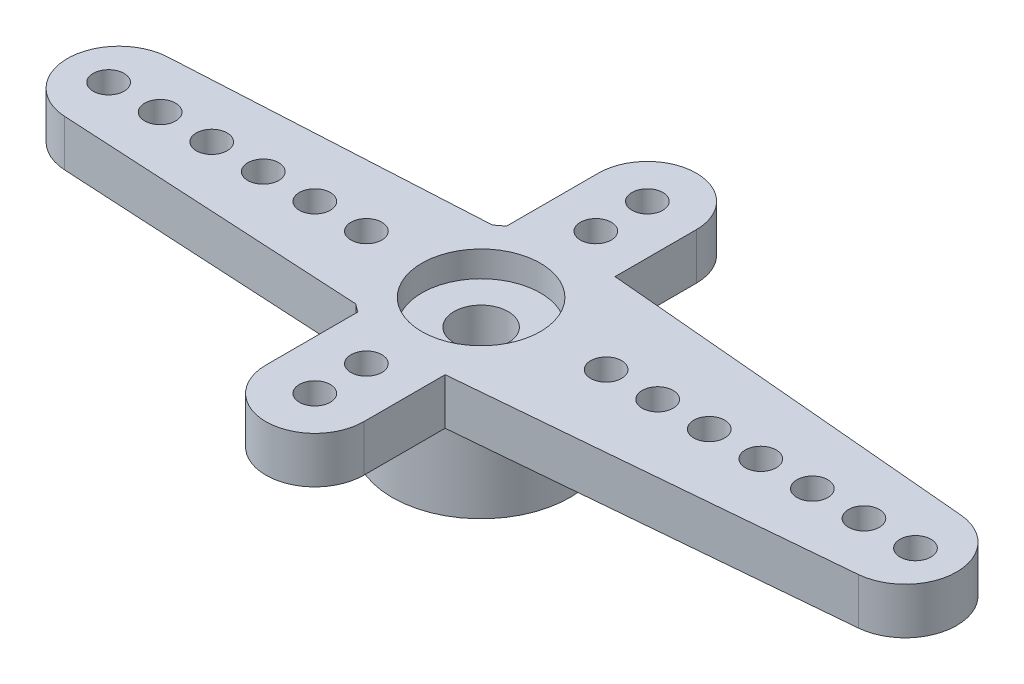
SolidWorks part; units mm, degrees
material "PVC Rígido"
ref_plane "Plano frontal" through (0, 0, 0) normal (0, 0, 1) x (1, 0, 0)
ref_plane "Plano superior" through (0, 0, 0) normal (0, 1, 0) x (1, 0, 0)
ref_plane "Plano direito" through (0, 0, 0) normal (1, 0, 0) x (0, 0, -1)
sketch "Esboço1" plane through (0, 0, 0) normal (0, 1, 0) x (1, 0, 0)
  line L0 (0, 0) -> (-14.05, 0) construction
  line L1 (-14.1591, 1.997) -> (-2.2091, 2.65)
  line L2 (-2.2091, -2.65) -> (-14.1591, -1.997)
  arc A0 (-2.2091, -2.65) -> (-2.2091, 2.65) centre (0, 0) ccw
  arc A1 (-14.1591, 1.997) -> (-14.1591, -1.997) centre (-14.05, 0) ccw
  dimension "D1" = 6.9
  dimension "D2" = 4
  dimension "D3" = 19.5
  dimension "D4" = 5.3
extrude "Ressalto-extrusão1" add sketch "Esboço1" against normal blind 1.8
sketch "Esboço2" plane through (0, -1.8, 0) normal (0, -1, 0) x (1, 0, 0)
  arc A0 (-2.2091, -2.65) -> (-2.2091, 2.65) centre (0, 0) ccw construction
  circle A1 centre (0, 0) radius 3.45
extrude "Ressalto-extrusão2" add sketch "Esboço2" along normal offset from surface (3.2 mm away) 5 up to face at (-7.242, 0, 0)
hole_wizard "Furo1" positions "Esboço9" profile "Esboço10" legacy end condition through all
sketch "Esboço9" plane through (0, 0, 0) normal (0, 1, 0) x (1, 0, 0)
  line L1 (-14.45, 0) -> (0, 0) construction
  arc A2 (-14.1591, 1.997) -> (-14.1591, -1.997) centre (-14.05, 0) ccw construction
  point P0 (-14.45, 0)
  point P19 (-16.05, 0)
  dimension "D1" = 1.6
sketch "Esboço10" plane through (-14.45, 0, 0) normal (1, 0, 0) x (0, 0, 1)
  line L0 (0, 0) -> (0, 5)
  line L1 (0, 5) -> (0.6, 5)
  line L2 (0.6, 5) -> (0.6, 0)
  line L3 (0.6, 0) -> (0, 0)
  line L4 (0, 110) -> (0, -10) construction
  dimension "Diameter" = 1.2
  dimension "Depth" = 5
pattern_linear "Padrão linear1" count 6 spacing 2 along (1, 0, 0) of "Furo1"
sketch "Esboço12" plane through (0, 0, 0) normal (0, 1, 0) x (1, 0, 0)
  line L0 (0.3041, 3.4366) -> (16.6263, 1.9922)
  line L1 (16.6263, -1.9922) -> (0.3041, -3.4366)
  arc A0 (-2.2091, -2.65) -> (-2.2091, 2.65) centre (0, 0) ccw construction
  arc A1 (0.3041, -3.4366) -> (0.3041, 3.4366) centre (0, 0) ccw
  arc A2 (16.6263, 1.9922) -> (16.6263, -1.9922) centre (16.45, 0) cw
  arc A3 (-14.1591, 1.997) -> (-14.1591, -1.997) centre (-14.05, 0) ccw construction
  dimension "D1" = 2
  dimension "D2" = 34.5
extrude "Ressalto-extrusão3" add sketch "Esboço12" against normal blind 1.8
hole_wizard "Furo2" positions "Esboço13" profile "Esboço14" legacy end condition through all
sketch "Esboço13" plane through (0, 0, 0) normal (0, 1, 0) x (1, 0, 0)
  line L0 (0, 0) -> (16.85, 0) construction
  arc A0 (16.6263, -1.9922) -> (16.6263, 1.9922) centre (16.45, 0) ccw construction
  point P0 (16.85, 0)
  point P6 (18.45, 0)
  dimension "D1" = 1.6
sketch "Esboço14" plane through (16.85, 0, 0) normal (1, 0, 0) x (0, 0, 1)
  line L0 (0, 0) -> (0, 5)
  line L1 (0, 5) -> (0.6, 5)
  line L2 (0.6, 5) -> (0.6, 0)
  line L3 (0.6, 0) -> (0, 0)
  line L4 (0, 110) -> (0, -10) construction
  dimension "Diameter" = 1.2
  dimension "Depth" = 5
pattern_linear "Padrão linear2" count 7 spacing 2 along (-1, 0, 0) of "Furo2"
sketch "Esboço16" plane through (0, 0, 0) normal (0, 1, 0) x (1, 0, 0)
  line L0 (0, -6.45) -> (0, 6.45) construction
  line L1 (-1.9, -6.45) -> (-1.9, 6.45)
  line L2 (1.9, -6.45) -> (1.9, 6.45)
  arc A0 (-1.9, -6.45) -> (1.9, -6.45) centre (0, -6.45) ccw
  arc A1 (1.9, 6.45) -> (-1.9, 6.45) centre (0, 6.45) ccw
  point P2 (0, 0)
  dimension "D2" = 16.7
  dimension "D1" = 3.8
extrude "Ressalto-extrusão4" add sketch "Esboço16" against normal up to surface (1.8 mm away) up to face at (14.85, -1.8, 0.6)
hole_wizard "Furo3" positions "Esboço17" profile "Esboço18" legacy end condition through all
sketch "Esboço17" plane through (0, 0, 0) normal (0, 1, 0) x (1, 0, 0)
  point P0 (0, -6.45)
sketch "Esboço18" plane through (0, 0, 6.45) normal (1, 0, 0) x (0, 0, 1)
  line L0 (0, 0) -> (0, 5)
  line L1 (0, 5) -> (0.6, 5)
  line L2 (0.6, 5) -> (0.6, 0)
  line L3 (0.6, 0) -> (0, 0)
  line L4 (0, 110) -> (0, -10) construction
  dimension "Diameter" = 1.2
  dimension "Depth" = 5
pattern_linear "Padrão linear3" count 2 spacing 2 along (0, 0, -1) of "Furo3"
pattern_circular "PadrãoCircular1" count 2 over 360 about axis through (0, 0, 0) along (0, 1, 0) of "Padrão linear3", "Furo3"
hole_wizard "Furo4" positions "Esboço3" profile "Esboço4" legacy
sketch "Esboço3" plane through (0, -5, 0) normal (0, -1, 0) x (-1, 0, 0)
  point P0 (0, 0)
sketch "Esboço4" plane through (0, -5, 0) normal (1, 0, 0) x (0, 0, -1)
  line L0 (0, 0) -> (0, 2)
  line L1 (0, 2) -> (2.475, 2)
  line L2 (2.475, 2) -> (2.475, 0)
  line L3 (2.475, 0) -> (0, 0)
  line L4 (0, 110) -> (0, -10) construction
  dimension "Diameter" = 4.95
  dimension "Depth" = 2
hole_wizard "Furo5" positions "Esboço5" profile "Esboço6" legacy
sketch "Esboço5" plane through (0, 0, 0) normal (0, 1, 0) x (1, 0, 0)
  point P0 (0, 0)
sketch "Esboço6" plane through (0, 0, 0) normal (1, 0, 0) x (0, 0, 1)
  line L0 (0, 0) -> (0, 1)
  line L1 (0, 1) -> (2.3, 1)
  line L2 (2.3, 1) -> (2.3, 0)
  line L3 (2.3, 0) -> (0, 0)
  line L4 (0, 110) -> (0, -10) construction
  dimension "Diameter" = 4.6
  dimension "Depth" = 1
hole_wizard "Furo6" positions "Esboço7" profile "Esboço8" legacy end condition through all
sketch "Esboço7" plane through (0, 0, 0) normal (0, 1, 0) x (1, 0, 0)
  point P0 (0, 0)
sketch "Esboço8" plane through (0, 0, 0) normal (1, 0, 0) x (0, 0, 1)
  line L0 (0, 0) -> (0, 5)
  line L1 (0, 5) -> (1.05, 5)
  line L2 (1.05, 5) -> (1.05, 0)
  line L3 (1.05, 0) -> (0, 0)
  line L4 (0, 110) -> (0, -10) construction
  dimension "Diameter" = 2.1
  dimension "Depth" = 5
sketch "Esboço11" plane through (0, -5, 0) normal (0, -1, 0) x (1, 0, 0)
  line L0 (-0.0981, 2.4731) -> (0, 2.375)
  line L1 (0, 2.375) -> (0.0981, 2.4731)
  line L2 (0, 0) -> (0, 2.475) construction
  circle A0 centre (0, 0) radius 2.375 construction
  circle A1 centre (0, 0) radius 2.475
  arc A2 (0.0981, 2.4731) -> (-0.0981, 2.4731) centre (0, 0) ccw
  dimension "D3" = 4.75
  dimension "D2" = 0.1
  dimension "D1" = 0
extrude "Ressalto-extrusão5" add sketch "Esboço11" against normal up to surface (2 mm away) up to face at (0, -3, 1.05)
pattern_circular "PadrãoCircular2" count 60 over 360 about axis through (0, 0, 0) along (0, 1, 0) of "Ressalto-extrusão5"
